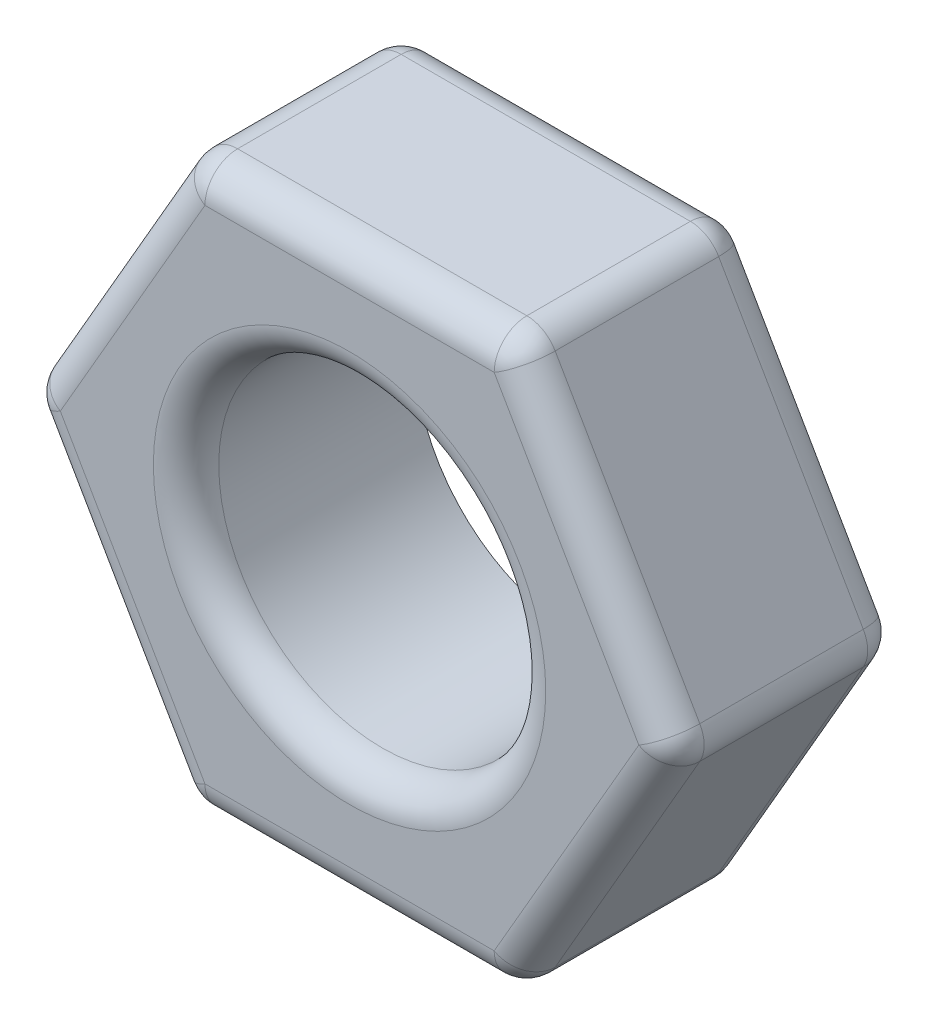
SolidWorks part; units mm, degrees
material "S235JR"
ref_plane "Front Plane" through (0, 0, 0) normal (0, 0, 1) x (1, 0, 0)
ref_plane "Top Plane" through (0, 0, 0) normal (0, 1, 0) x (1, 0, 0)
ref_plane "Right Plane" through (0, 0, 0) normal (1, 0, 0) x (0, 0, -1)
sketch "Sketch1" plane through (0, 0, 0) normal (0, 0, 1) x (1, 0, 0)
  line L1 (10, 0) -> (5, 8.6603)
  line L2 (5, 8.6603) -> (-5, 8.6603)
  line L3 (-5, 8.6603) -> (-10, 0)
  line L4 (-10, 0) -> (-5, -8.6603)
  line L5 (-5, -8.6603) -> (5, -8.6603)
  line L6 (5, -8.6603) -> (10, 0)
  circle A0 centre (0, 0) radius 5
  circle A1 centre (0, 0) radius 8.6603 construction
  dimension "D1" = 10
  dimension "D2" = 20
extrude "Boss-Extrude1" add sketch "Sketch1" along normal blind 7
fillet "Fillet1" radius 1 7 edges at (5, 0, 7) (10, 0, 3.5) (5, -8.6603, 3.5) (-5, -8.6603, 3.5) (-10, 0, 3.5) (-5, 8.6603, 3.5) (5, 8.6603, 3.5)
fillet "Fillet2" radius 1 24 edges at (-4.9226, 8.5263, 0) (0, 8.6603, 0) (4.9226, 8.5263, 0) (7.5, 4.3301, 0) (9.8453, 0, 0) (7.5, -4.3301, 0) (4.9226, -8.5263, 0) (0, -8.6603, 0) (-4.9226, -8.5263, 0) (-7.5, -4.3301, 0) (-9.8453, 0, 0) (-4.9226, 8.5263, 7) (0, 8.6603, 7) (4.9226, 8.5263, 7) (7.5, 4.3301, 7) (9.8453, 0, 7) (7.5, -4.3301, 7) (4.9226, -8.5263, 7) (0, -8.6603, 7) (-4.9226, -8.5263, 7) (-7.5, -4.3301, 7) (-9.8453, 0, 7) (-7.5, 4.3301, 0) (-7.5, 4.3301, 7)
